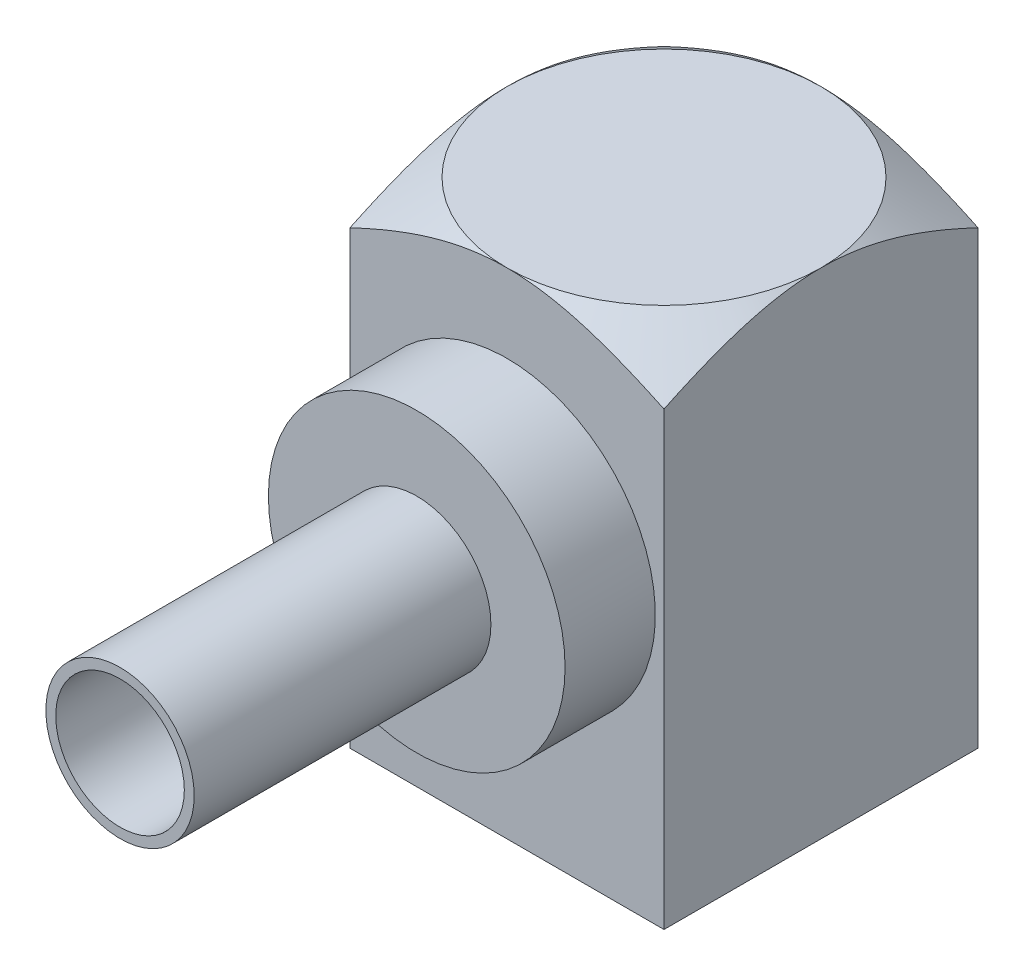
SolidWorks part; units mm, degrees
material "黄铜"
ref_plane "前视基准面" through (0, 0, 0) normal (0, 0, 1) x (1, 0, 0)
ref_plane "上视基准面" through (0, 0, 0) normal (0, 1, 0) x (1, 0, 0)
ref_plane "右视基准面" through (0, 0, 0) normal (1, 0, 0) x (0, 0, -1)
sketch "草图1" plane through (0, 0, 0) normal (0, 1, 0) x (1, 0, 0)
  line L1 (3.175, -3.175) -> (-3.175, -3.175)
  line L2 (3.175, -3.175) -> (3.175, 3.175)
  line L3 (3.175, 3.175) -> (-3.175, 3.175)
  line L4 (-3.175, -3.175) -> (-3.175, 3.175)
  line L5 (3.175, -3.175) -> (-3.175, 3.175) construction
  line L6 (3.175, 3.175) -> (-3.175, -3.175) construction
  circle A0 centre (0, 0) radius 3.175
  point P0 (0, 0)
  dimension "D1" = 6.35
  dimension "D2" = 6.35
sketch "草图2" plane through (0, 0, 0) normal (0, 1, 0) x (1, 0, 0)
  line L4 (-3.175, -3.175) -> (3.175, -3.175)
  line L5 (-3.175, 3.175) -> (-3.175, -3.175)
  line L6 (3.175, 3.175) -> (-3.175, 3.175)
  line L7 (3.175, -3.175) -> (3.175, 3.175)
  line L8 (-3.175, -3.175) -> (3.175, -3.175)
  line L9 (-3.175, 3.175) -> (-3.175, -3.175)
  line L10 (3.175, 3.175) -> (-3.175, 3.175)
  line L11 (3.175, -3.175) -> (3.175, 3.175)
  dimension "D2" = 0
extrude "凸台-拉伸1" add sketch "草图2" along normal blind 10
sketch "草图3" plane through (0, 10, 0) normal (0, 1, 0) x (1, 0, 0)
  line L0 (0, 0) -> (5.0421, 0)
  line L4 (-3.175, -3.175) -> (3.175, -3.175)
  line L5 (-3.175, 3.175) -> (-3.175, -3.175)
  line L6 (3.175, 3.175) -> (-3.175, 3.175)
  line L7 (3.175, -3.175) -> (3.175, 3.175)
  line L8 (-3.175, -3.175) -> (3.175, -3.175)
  line L9 (-3.175, 3.175) -> (-3.175, -3.175)
  line L10 (3.175, 3.175) -> (-3.175, 3.175)
  line L11 (3.175, -3.175) -> (3.175, 3.175)
  circle A1 centre (0, 0) radius 3.175
  circle A2 centre (0, 0) radius 3.175
  dimension "D1" = 0
  dimension "D2" = 0
sketch "草图5" plane through (0, 0, 0) normal (0, 0, 1) x (1, 0, 0)
  line L0 (3.175, 10) -> (5.2489, 14.5885)
  line L1 (0, 10) -> (5.0421, 10) construction
  line L2 (3.175, 10) -> (-3.175, 10) construction
  line L5 (3.175, 10) -> (5.2489, 8.6042)
  line L6 (5.2489, 8.6042) -> (5.2489, 14.5885)
ref_axis "基准轴1" through (0, 15.4277, 0) along (0, -1, 0)
revolve "切除-旋转1" cut sketch "草图5" angle 360 about axis through (0, 15.4277, 0) along (0, -1, 0)
sketch "草图6" plane through (0, 0, 0) normal (0, 0, 1) x (1, 0, 0)
  line L0 (0, 15.4277) -> (0, -0.7347) construction
  circle A0 centre (0, 5.4167) radius 3
  dimension "D1" = 6
extrude "凸台-拉伸2" add sketch "草图6" along normal blind 5
sketch "草图7" plane through (0, 0, 5) normal (0, 0, 1) x (1, 0, 0)
  circle A0 centre (0, 5.4167) radius 1.5
  circle A1 centre (0, 5.4167) radius 1.3
  dimension "D2" = 2.6
  dimension "D1" = 3
extrude "凸台-拉伸3" add sketch "草图7" along normal blind 6
